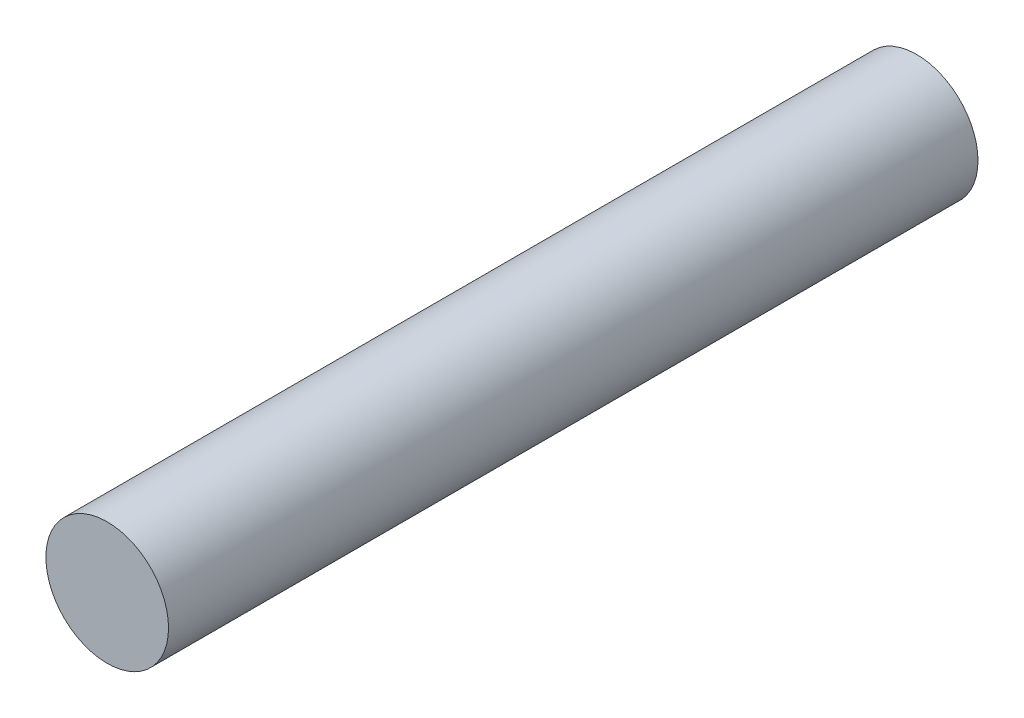
SolidWorks part; units mm, degrees
ref_plane "Front Plane" through (0, 0, 0) normal (0, 0, 1) x (1, 0, 0)
ref_plane "Top Plane" through (0, 0, 0) normal (0, 1, 0) x (1, 0, 0)
ref_plane "Right Plane" through (0, 0, 0) normal (1, 0, 0) x (0, 0, -1)
sketch "Sketch1" plane through (0, 0, 0) normal (0, 0, 1) x (1, 0, 0)
  circle A0 centre (-40.9832, 47.5012) radius 2.5
extrude "Boss-Extrude1" add sketch "Sketch1" along normal blind 33
